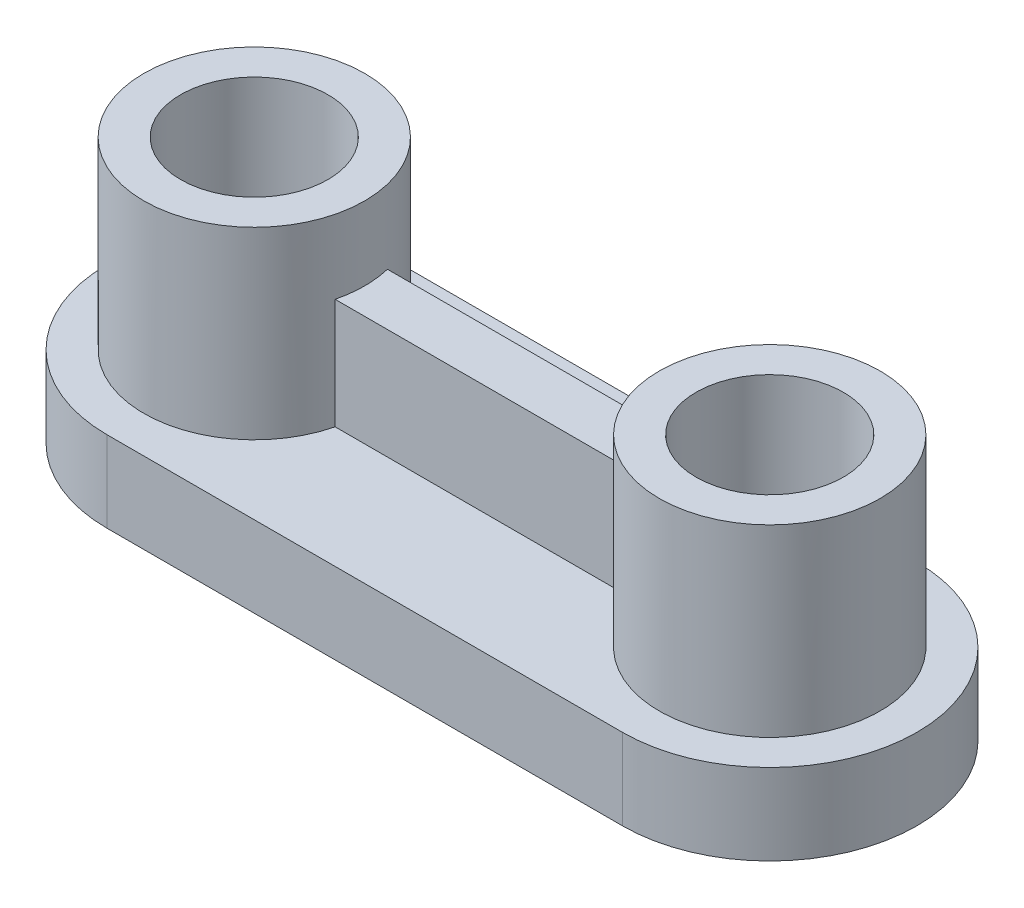
SolidWorks part; units mm, degrees
ref_plane "Front Plane" through (0, 0, 0) normal (0, 0, 1) x (1, 0, 0)
ref_plane "Top Plane" through (0, 0, 0) normal (0, 1, 0) x (1, 0, 0)
ref_plane "Right Plane" through (0, 0, 0) normal (1, 0, 0) x (0, 0, -1)
sketch "Sketch3" plane through (0, 0, 0) normal (0, 1, 0) x (1, 0, 0)
  line L8 (-266.7579, 20) -> (-196.7579, 20)
  line L9 (-266.7579, -20) -> (-196.7579, -20)
  circle A0 centre (-266.7579, 0) radius 7.5
  circle A1 centre (-266.7579, 0) radius 10
  circle A2 centre (-266.7579, 0) radius 15
  circle A3 centre (-196.7579, 0) radius 7.5
  circle A4 centre (-196.7579, 0) radius 10
  circle A5 centre (-196.7579, 0) radius 15
  arc A6 (-266.7579, -20) -> (-266.7579, 20) centre (-266.7579, 0) cw
  arc A7 (-196.7579, 20) -> (-196.7579, -20) centre (-196.7579, 0) cw
  dimension "D1" = 15
  dimension "D2" = 20
  dimension "D3" = 30
  dimension "D4" = 30
  dimension "D5" = 20
  dimension "D6" = 15
  dimension "D7" = 70
extrude "Boss-Extrude2" add sketch "Sketch3" along normal blind 11 contours L9 A7 L8 A6
sketch "Sketch5" plane through (0, 11, 0) normal (0, 1, 0) x (1, 0, 0)
  circle A0 centre (-196.7579, 0) radius 15
  circle A1 centre (-266.7579, 0) radius 15
  dimension "D1" = 30
  dimension "D2" = 30
extrude "Boss-Extrude4" add sketch "Sketch5" along normal blind 25 contours A0 | A1
sketch "Sketch6" plane through (0, 36, 0) normal (0, 1, 0) x (1, 0, 0)
  circle A0 centre (-266.7579, 0) radius 10
  circle A2 centre (-196.7579, 0) radius 10
  dimension "D1" = 20
  dimension "D2" = 20
extrude "Cut-Extrude1" cut sketch "Sketch6" against normal blind 20
sketch "Sketch7" plane through (0, 16, 0) normal (0, 1, 0) x (1, 0, 0)
  circle A1 centre (-196.7579, 0) radius 7.5
  circle A3 centre (-266.7579, 0) radius 7.5
  dimension "D1" = 15
  dimension "D2" = 15
extrude "Cut-Extrude2" cut sketch "Sketch7" against normal through all
sketch "Sketch8" plane through (0, 11, 0) normal (0, 1, 0) x (1, 0, 0)
  line L0 (-252.1923, -3.5837) -> (-252.1923, 3.5)
  line L1 (-252.1923, 3.5) -> (-211.3235, 3.5)
  line L2 (-211.3235, 3.5) -> (-211.3235, -3.5837)
  line L3 (-252.1923, -3.5837) -> (-211.3235, -3.5837)
  circle A3 centre (-266.7579, 0) radius 15 construction
  circle A4 centre (-196.7579, 0) radius 15 construction
extrude "Boss-Extrude5" add sketch "Sketch8" along normal blind 15
sketch "Sketch9" plane through (0, 0, 0) normal (0, -1, 0) x (1, 0, 0)
  line L0 (-249.1078, 9.0234) -> (-249.1078, -8.9766)
  line L2 (-249.1078, -8.9766) -> (-213.1078, -8.9766)
  line L7 (-249.1078, 9.0234) -> (-213.1078, 9.0234)
  line L8 (-213.1078, 9.0234) -> (-213.1078, -8.9766)
  dimension "D1" = 36
  dimension "D2" = 18
extrude "Cut-Extrude3" cut sketch "Sketch9" against normal blind 5 contours L2 L8 L7 L0
